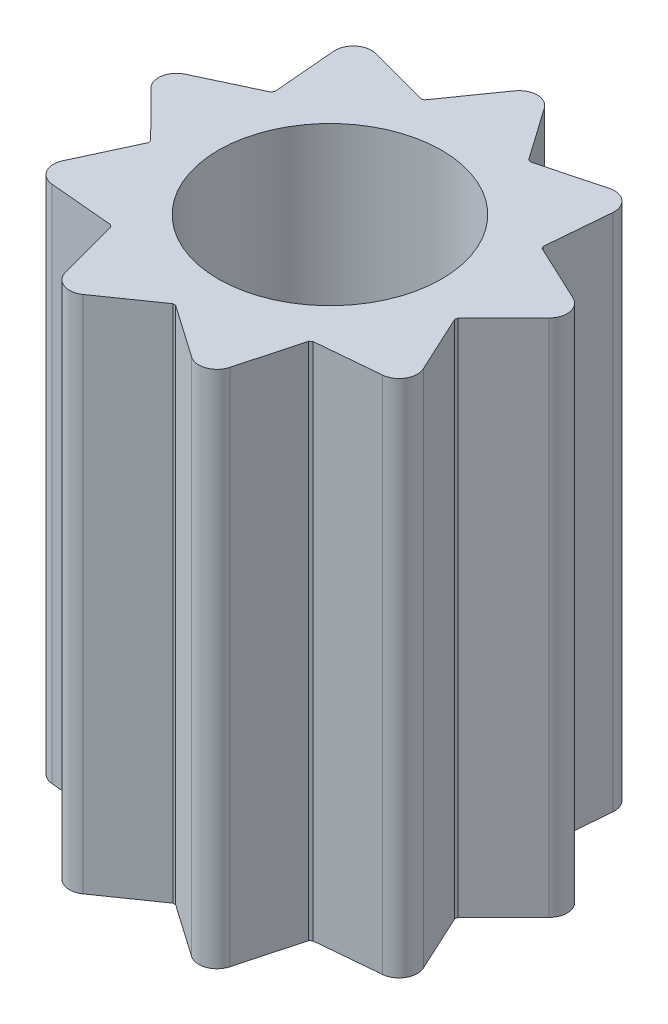
SolidWorks part; units mm, degrees
ref_plane "Front Plane" through (0, 0, 0) normal (0, 0, 1) x (1, 0, 0)
ref_plane "Top Plane" through (0, 0, 0) normal (0, 1, 0) x (1, 0, 0)
ref_plane "Right Plane" through (0, 0, 0) normal (1, 0, 0) x (0, 0, -1)
sketch "Sketch1" plane through (0, 0, 0) normal (0, 1, 0) x (1, 0, 0)
  line L0 (0, 2.25) -> (0, 4.25) construction
  line L1 (0, 4.25) -> (1, 2.8284)
  line L2 (0, 4.25) -> (-1, 2.8284)
  line L3 (2.7318, 3.2557) -> (1.052, 2.8095)
  line L4 (2.7318, 3.2557) -> (2.5841, 1.5239)
  line L5 (4.1854, 0.738) -> (2.6118, 1.476)
  line L6 (4.1854, 0.738) -> (2.9591, -0.4937)
  line L7 (3.6806, -2.125) -> (2.9495, -0.5482)
  line L8 (3.6806, -2.125) -> (1.9495, -2.2802)
  line L9 (1.4536, -3.9937) -> (1.9071, -2.3158)
  line L10 (1.4536, -3.9937) -> (0.0277, -2.9999)
  line L11 (-1.4536, -3.9937) -> (-0.0277, -2.9999)
  line L12 (-1.4536, -3.9937) -> (-1.9071, -2.3158)
  line L13 (-3.6806, -2.125) -> (-1.9495, -2.2802)
  line L14 (-3.6806, -2.125) -> (-2.9495, -0.5482)
  line L15 (-4.1854, 0.738) -> (-2.9591, -0.4937)
  line L16 (-4.1854, 0.738) -> (-2.6118, 1.476)
  line L17 (-2.7318, 3.2557) -> (-2.5841, 1.5239)
  line L18 (-2.7318, 3.2557) -> (-1.052, 2.8095)
  circle A0 centre (0, 0) radius 4.25 construction
  circle A1 centre (0, 0) radius 3
  circle A3 centre (0, 0) radius 2.15
  point P26 (0, 0)
  dimension "D1" = 8.5
  dimension "D2" = 6
  dimension "D4" = 2
  dimension "D6" = 4.3
  dimension "D3" = 2
  dimension "D5" = 9
extrude "Boss-Extrude1" add sketch "Sketch1" along normal blind 10 contours A1 L1 L2 | A1 L4 L3 | A1 L6 L5 | A1 L8 L7 | A1 L10 L9 | A1 L12 L11 | A1 A3 | A1 L14 L13 | A1 L16 L15 | A1 L18 L17
fillet "Fillet1" radius 0.35 9 edges at (2.7318, 5, -3.2557) (4.1854, 5, -0.738) (3.6806, 5, 2.125) (0, 5, -4.25) (-1.4536, 5, 3.9937) (1.4536, 5, 3.9937) (-2.7318, 5, -3.2557) (-3.6806, 5, 2.125) (-4.1854, 5, -0.738)
